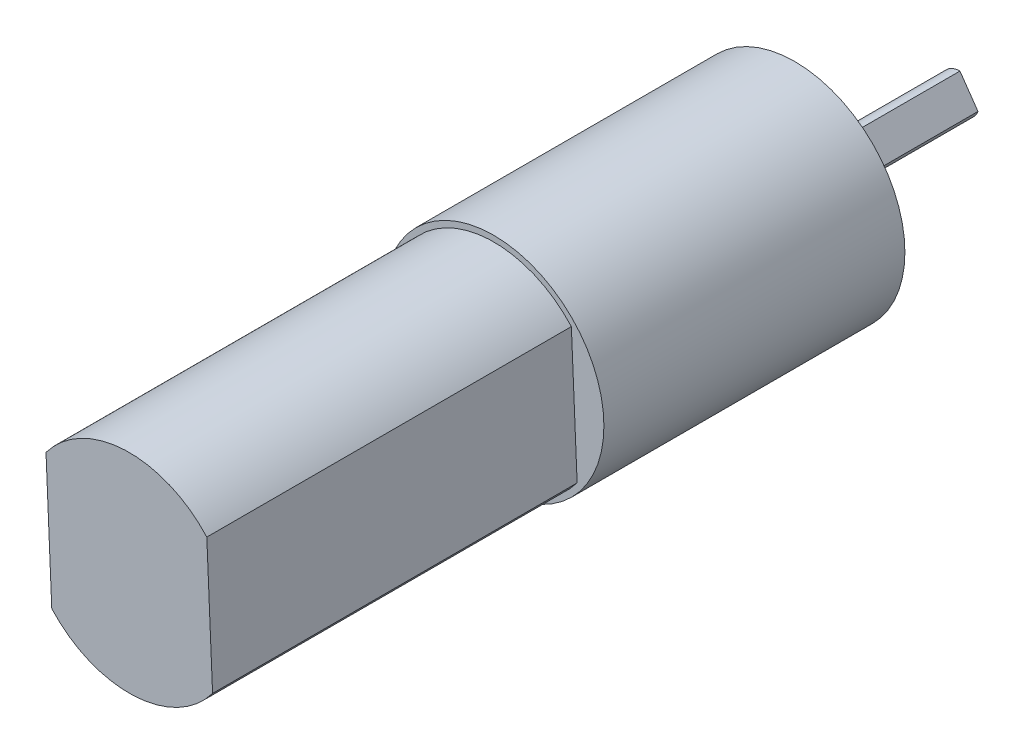
SolidWorks part; units mm, degrees
ref_plane "Front Plane" through (0, 0, 0) normal (0, 0, 1) x (1, 0, 0)
ref_plane "Top Plane" through (0, 0, 0) normal (0, 1, 0) x (1, 0, 0)
ref_plane "Right Plane" through (0, 0, 0) normal (1, 0, 0) x (0, 0, -1)
sketch "Sketch1" plane through (0, 0, 0) normal (0, 0, 1) x (1, 0, 0)
  circle A0 centre (0, 0) radius 8
  dimension "D1" = 16
extrude "Boss-Extrude1" add sketch "Sketch1" along normal blind 21.88
sketch "Sketch2" plane through (0, 0, 21.88) normal (0, 0, 1) x (1, 0, 0)
  line L0 (5.6345, 5.0704) -> (6.0544, -4.5608)
  line L1 (-6.0544, 4.5608) -> (-5.6345, -5.0704)
  arc A0 (5.6345, 5.0704) -> (-6.0544, 4.5608) centre (0, 0) ccw
  arc A2 (-5.6345, -5.0704) -> (6.0544, -4.5608) centre (0, 0) ccw
  dimension "D1" = 15.16
  dimension "D2" = 11.7
  dimension "D3" = 5.85
extrude "Boss-Extrude2" add sketch "Sketch2" along normal blind 26.5
sketch "Sketch3" plane through (0, 0, 0) normal (0, 0, -1) x (-1, 0, 0)
  circle A0 centre (0, 0) radius 2.835
  dimension "D1" = 5.67
extrude "Boss-Extrude3" add sketch "Sketch3" along normal blind 2
sketch "Sketch4" plane through (0, 0, -2) normal (0, 0, -1) x (-1, 0, 0)
  line L0 (0, 1.4) -> (-1.313, -0.4857)
  arc A0 (-1.313, -0.4857) -> (0, 1.4) centre (0, 0) ccw
  dimension "D1" = 2.8
  dimension "D2" = 0.8
extrude "Boss-Extrude4" add sketch "Sketch4" along normal blind 10
hole_wizard "Ø2.05 (2.05) Diameter Hole1" positions "Sketch6" profile "Sketch5" hole size "Ø2.05" standard "ISO"
sketch "Sketch6" plane through (0, 0, 0) normal (0, 0, -1) x (-1, 0, 0)
  point P0 (-5.5, 0)
  point P2 (5.5, 0)
  dimension "D1" = 11
  dimension "D2" = 5.5
sketch "Sketch5" plane through (5.5, 0, 0) normal (1, 0, 0) x (0, 1, 0)
  line L0 (0, 0) -> (0, 3.6159)
  line L1 (0, 3.6159) -> (1.025, 3)
  line L2 (1.025, 3) -> (1.025, 0)
  line L5 (1.025, 0) -> (0, 0)
  line L10 (0, 3.6159) -> (-1.025, 3) construction
  line L11 (0, -6.35) -> (0, 107.95) construction
  dimension "Hole Dia." = 2.05
  dimension "Hole Depth" = 3
  dimension "Drill Angle" = 118
